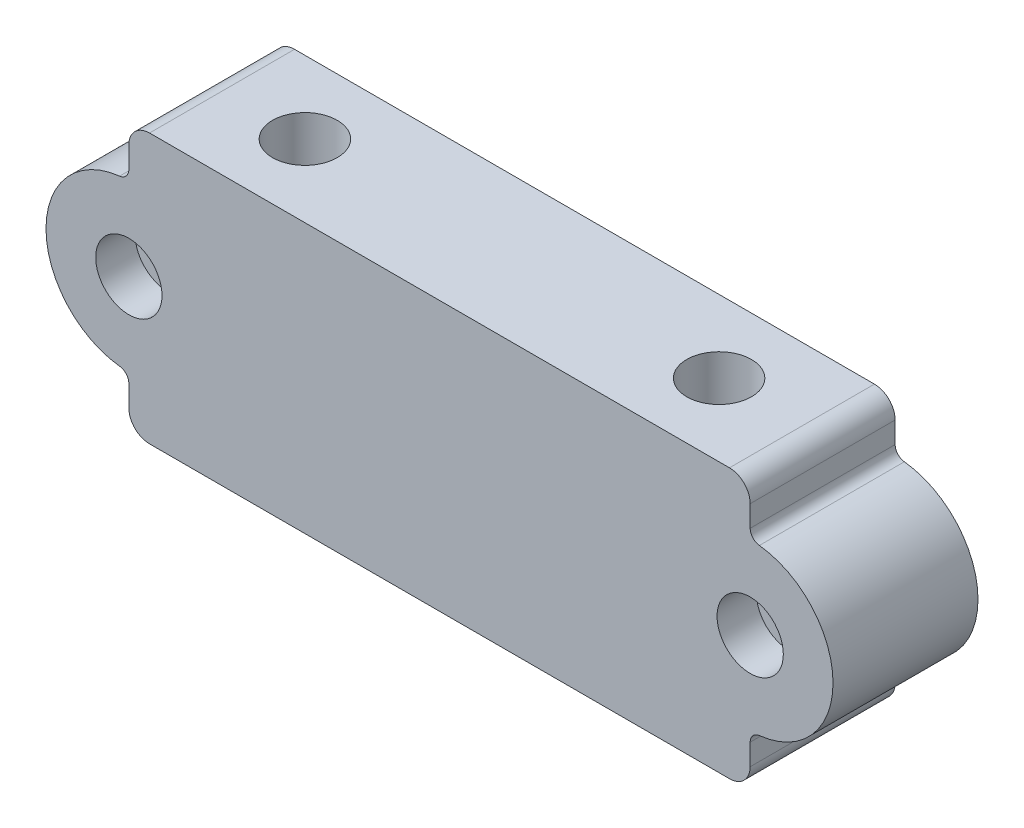
SolidWorks part; units mm, degrees
material "6061-T6 (SS)"
ref_plane "X-Y Datum" through (0, 0, 0) normal (0, 0, 1) x (1, 0, 0)
ref_plane "X-Z Datum" through (0, 0, 0) normal (0, 1, 0) x (1, 0, 0)
ref_plane "Y-Z Datum" through (0, 0, 0) normal (1, 0, 0) x (0, 0, -1)
other "Graphic1"
other "Graphic (Closed) -1"
other "Graphic2"
other "Graphic (Closed) -2"
other "Graphic3"
other "Graphic (Closed) -3"
sketch "Sketch1" plane through (0, 0, 0) normal (0, 1, 0) x (1, 0, 0)
  line L0 (101.6, 8.89) -> (76.2, 8.89) construction
  line L1 (101.6, 17.78) -> (0, 17.78)
  line L2 (101.6, 17.78) -> (101.6, 0)
  line L3 (101.6, 0) -> (0, 0)
  line L5 (0, 31.6293) -> (0, -17.6841) construction
  line L6 (0, 17.78) -> (0, 0)
  line L7 (76.2, 8.89) -> (25.4, 8.89) construction
  line L8 (25.4, 8.89) -> (0, 8.89) construction
  circle A0 centre (76.2, 8.89) radius 3.9688
  circle A1 centre (25.4, 8.89) radius 3.9687
  point P1 (0, 0)
  point P10 (25.6866, 8.89)
  point P11 (31.75, 8.89)
  point P12 (50.8, 8.89)
  point P13 (50.8, 17.78)
  dimension "D3" = 7.9375
  dimension "D1" = 101.6
  dimension "D2" = 17.78
  dimension "D4" = 50.8
extrude "Boss-Extrude1" add sketch "Sketch1" against normal blind 33.02
sketch "Sketch2" plane through (0, 0, 0) normal (0, 0, 1) x (1, 0, 0)
  line L4 (0, -33.02) -> (0, 0) construction
  line L5 (0, -33.02) -> (101.6, -33.02) construction
  line L8 (101.6, -33.02) -> (101.6, 0) construction
  circle A0 centre (88.9, -16.51) radius 2.4892
  circle A1 centre (12.7, -16.51) radius 2.4892
  point P30 (0, 0)
  point P31 (19.3935, -16.51)
  dimension "D3" = 4.9784
  dimension "D1" = 12.7
  dimension "D5" = 16.51
  dimension "D6" = 12.7
  dimension "D2" = 16.51
extrude "Cut-Extrude1" cut sketch "Sketch2" against normal up to surface (17.78 mm away) up to face at (50.8, -16.51, -17.78)
sketch "Sketch3" plane through (0, 0, 0) normal (0, 0, 1) x (1, 0, 0)
  circle A0 centre (88.9, -16.51) radius 4.064
  circle A3 centre (12.7, -16.51) radius 4.064
  circle A4 centre (12.7, -16.51) radius 2.4892 construction
  dimension "D1" = 8.128
extrude "Cut-Extrude2" cut sketch "Sketch3" against normal blind 4.826
ref_plane "Plane1" through (0, -16.51, 0) normal (0, 1, 0) x (1, 0, 0)
ref_plane "Plane2" through (0, -16.51, 0) normal (0, 1, 0) x (1, 0, 0)
ref_point "Point3"
ref_point "Point4"
sketch "Sketch5" plane through (0, 0, 0) normal (0, 0, 1) x (1, 0, 0)
  line L8 (0, -33.02) -> (101.6, -33.02) construction
  line L18 (0, -33.02) -> (0, 0) construction
  line L19 (50.8, 0) -> (50.8, -33.02) construction
  line L20 (0, 0) -> (101.6, 0) construction
  line B0 (12.7, -5.1508) -> (12.7, 0)
  line B1 (0, 0) -> (12.7, 0)
  line B2 (0, -33.02) -> (0, 0)
  line B3 (12.7, -33.02) -> (0, -33.02)
  line B4 (12.7, -27.8692) -> (12.7, -33.02)
  arc B5 (12.7, -5.1508) -> (11.5711, -6.4129) centre (11.43, -5.1508) cw
  arc B6 (12.7, -27.8692) -> (11.5711, -26.6071) centre (11.43, -27.8692) ccw
  arc B7 (11.5711, -26.6071) -> (11.5711, -6.4129) centre (12.7, -16.51) cw
  line B8 (88.9, -5.1508) -> (88.9, 0)
  line B9 (101.6, 0) -> (88.9, 0)
  line B10 (101.6, -33.02) -> (101.6, 0)
  line B11 (88.9, -33.02) -> (101.6, -33.02)
  line B12 (88.9, -27.8692) -> (88.9, -33.02)
  arc B13 (88.9, -5.1508) -> (90.0289, -6.4129) centre (90.17, -5.1508) ccw
  arc B14 (88.9, -27.8692) -> (90.0289, -26.6071) centre (90.17, -27.8692) cw
  arc B15 (90.0289, -26.6071) -> (90.0289, -6.4129) centre (88.9, -16.51) ccw
sketch_block_instance "Block2-1"
sketch_block "Block2"
sketch_block_instance "Block2-2"
extrude "Cut-Extrude3" cut sketch "Sketch5" against normal through all
fillet "Fillet1" radius 2.54 4 edges at (12.7, 0, -8.89) (88.9, 0, -8.89) (88.9, -33.02, -8.89) (12.7, -33.02, -8.89)
